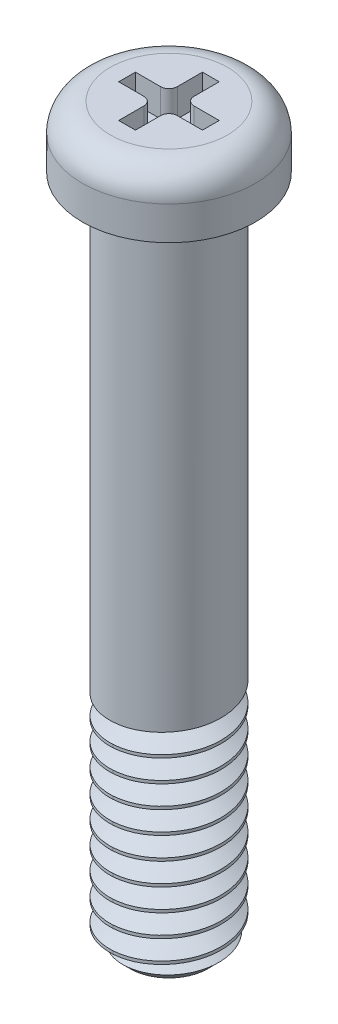
SolidWorks part; units mm, degrees
ref_plane "前视基准面" through (0, 0, 0) normal (0, 0, 1) x (1, 0, 0)
ref_plane "上视基准面" through (0, 0, 0) normal (0, 1, 0) x (1, 0, 0)
ref_plane "右视基准面" through (0, 0, 0) normal (1, 0, 0) x (0, 0, -1)
sketch "草图1" plane through (0, 0, 0) normal (0, 1, 0) x (1, 0, 0)
  circle A0 centre (0, 0) radius 1.55
  dimension "D1" = 3.1
extrude "凸台-拉伸1" add sketch "草图1" along normal blind 1.1
sketch "草图2" plane through (0, 0, 0) normal (0, -1, 0) x (1, 0, 0)
  circle A0 centre (0, 0) radius 1
  dimension "D1" = 2
extrude "凸台-拉伸2" add sketch "草图2" along normal blind 12
sketch "草图4" plane through (0, -12, 0) normal (0, -1, 0) x (1, 0, 0)
  circle A0 centre (0, 0) radius 1
curve "螺旋线/涡状线1" pitch 0.4 height 4 turns 10
chamfer "倒角1" distance 0.3 angle 45 1 edges at (0, -12, -1)
sketch "草图5" plane through (0, 0, 0) normal (1, 0, 0) x (0, 0, -1)
  line L0 (1.142, -11.7448) -> (0.7, -12)
  line L3 (0.7, -12) -> (1.142, -12.2552)
  line L4 (1.142, -12.2552) -> (1.142, -11.7448)
sweep "切除-扫描1" cut profiles "草图5" path "螺旋线/涡状线1"
fillet "圆角2" radius 0.5 1 edges at (0, 1.1, 1.55)
sketch "草图6" plane through (0, 1.1, 0) normal (0, 1, 0) x (1, 0, 0)
  line L0 (-1.7535, 0) -> (1.8945, 0) construction
  line L1 (-0.15, 0.75) -> (0.15, 0.75)
  line L2 (-0.15, 0.75) -> (-0.15, 0.3)
  line L3 (-0.15, -0.75) -> (0.15, -0.75)
  line L4 (0.15, 0.75) -> (0.15, 0.3)
  line L5 (-0.75, 0.15) -> (-0.3, 0.15)
  line L6 (-0.75, 0.15) -> (-0.75, -0.15)
  line L7 (-0.75, -0.15) -> (-0.3, -0.15)
  line L8 (0.75, 0.15) -> (0.75, -0.15)
  line L9 (0, 2.0268) -> (0, -2.2114) construction
  line L10 (0.3, 0.15) -> (0.75, 0.15)
  line L11 (-0.15, -0.3) -> (-0.15, -0.75)
  line L12 (0.3, -0.15) -> (0.75, -0.15)
  line L13 (0.15, -0.3) -> (0.15, -0.75)
  arc A0 (-0.3, 0.15) -> (-0.15, 0.3) centre (-0.3, 0.3) ccw
  arc A1 (0.15, 0.3) -> (0.3, 0.15) centre (0.3, 0.3) ccw
  arc A2 (0.3, -0.15) -> (0.15, -0.3) centre (0.3, -0.3) ccw
  arc A3 (-0.15, -0.3) -> (-0.3, -0.15) centre (-0.3, -0.3) ccw
  dimension "D5" = 0.3
  dimension "D1" = 0.3
  dimension "D2" = 0.3
  dimension "D3" = 1.5
  dimension "D4" = 1.5
extrude "切除-拉伸1" cut sketch "草图6" against normal blind 0.5
